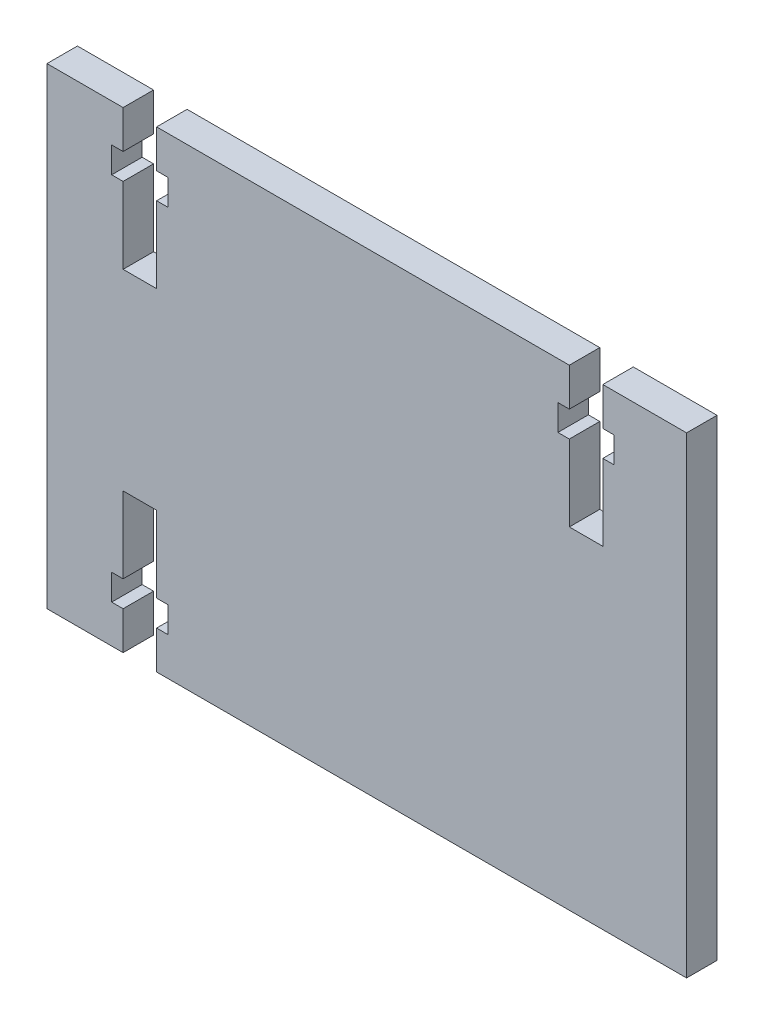
SolidWorks part; units mm, degrees
ref_plane "Front Plane" through (0, 0, 0) normal (0, 0, 1) x (1, 0, 0)
ref_plane "Top Plane" through (0, 0, 0) normal (0, 1, 0) x (1, 0, 0)
ref_plane "Right Plane" through (0, 0, 0) normal (1, 0, 0) x (0, 0, -1)
sketch "Sketch1" plane through (0, 0, 0) normal (0, 0, 1) x (1, 0, 0)
  line L1 (-41.5, 31) -> (42.5, 31)
  line L2 (-41.5, 31) -> (-41.5, -31)
  line L3 (-41.5, -31) -> (42.5, -31)
  line L4 (42.5, 31) -> (42.5, -31)
  dimension "D1" = 84
  dimension "D2" = 41.5
  dimension "D3" = 62
  dimension "D4" = 31
extrude "Boss-Extrude1" add sketch "Sketch1" along normal blind 4
sketch "Sketch2" plane through (0, 0, 4) normal (0, 0, 1) x (1, 0, 0)
  line L0 (0, 0) -> (-32.0835, 0) construction
  line L1 (42.5, -31) -> (27.5, -31)
  line L2 (42.5, -31) -> (42.5, -11)
  line L3 (42.5, -11) -> (27.5, -11)
  line L4 (27.5, -31) -> (27.5, -11)
  line L5 (0, 0) -> (0, 20.1899) construction
  dimension "D1" = 20
  dimension "D2" = 15
extrude "Cut-Extrude1" [suppressed] cut sketch "Sketch2" against normal blind 10
sketch "Sketch3" plane through (0, 0, 4) normal (0, 0, 1) x (1, 0, 0)
  line L0 (-29.3, 10.8) -> (-29.3, 25.6452) construction
  line L1 (-27.1, 22.6) -> (-27.1, 12.6)
  line L2 (-31.5, 26) -> (-31.5, 31)
  line L3 (-25.6, 26) -> (-27.1, 26)
  line L4 (-25.6, 22.6) -> (-25.6, 26)
  line L5 (-27.1, 22.6) -> (-25.6, 22.6)
  line L6 (-33, 26) -> (-31.5, 26)
  line L7 (-33, 22.6) -> (-33, 26)
  line L8 (-31.5, 22.6) -> (-33, 22.6)
  line L9 (-31.5, 12.6) -> (-27.1, 12.6)
  line L10 (-27.1, 31) -> (-27.1, 26)
  line L11 (-31.5, 31) -> (-27.1, 31)
  line L12 (-31.5, 12.6) -> (-31.5, 22.6)
  line L13 (42.5, 31) -> (-41.5, 31) construction
  line L14 (-41.5, 31) -> (-41.5, -31) construction
  line L15 (0, 0) -> (0, 26) construction
  line L16 (0, 0) -> (-34.9357, 0) construction
  line L17 (29.3, 10.8) -> (29.3, 25.6452) construction
  line L18 (31.5, 12.6) -> (31.5, 22.6)
  line L19 (31.5, 31) -> (27.1, 31)
  line L20 (27.1, 31) -> (27.1, 26)
  line L21 (31.5, 12.6) -> (27.1, 12.6)
  line L22 (31.5, 22.6) -> (33, 22.6)
  line L23 (33, 22.6) -> (33, 26)
  line L24 (33, 26) -> (31.5, 26)
  line L25 (27.1, 22.6) -> (25.6, 22.6)
  line L26 (25.6, 22.6) -> (25.6, 26)
  line L27 (25.6, 26) -> (27.1, 26)
  line L28 (31.5, 26) -> (31.5, 31)
  line L29 (27.1, 22.6) -> (27.1, 12.6)
  line L30 (-29.3, -10.8) -> (-29.3, -25.6452) construction
  line L31 (-31.5, -12.6) -> (-31.5, -22.6)
  line L32 (-31.5, -31) -> (-27.1, -31)
  line L33 (-27.1, -31) -> (-27.1, -26)
  line L34 (-31.5, -12.6) -> (-27.1, -12.6)
  line L35 (-31.5, -22.6) -> (-33, -22.6)
  line L36 (-33, -22.6) -> (-33, -26)
  line L37 (-33, -26) -> (-31.5, -26)
  line L38 (-27.1, -22.6) -> (-25.6, -22.6)
  line L39 (-25.6, -22.6) -> (-25.6, -26)
  line L40 (-25.6, -26) -> (-27.1, -26)
  line L41 (-31.5, -26) -> (-31.5, -31)
  line L42 (-27.1, -22.6) -> (-27.1, -12.6)
  dimension "D1" = 5
  dimension "D2" = 3.4
  dimension "D3" = 10
  dimension "D4" = 2.2
  dimension "D5" = 4.4
  dimension "D6" = 1.5
  dimension "D7" = 1.5
  dimension "D8" = 10
extrude "Cut-Extrude2" cut sketch "Sketch3" against normal blind 5
sketch "Sketch4" [suppressed] plane through (0, 0, 5) normal (0, 0, 1) x (1, 0, 0)
  line L1 (41.5, 31) -> (42.5, 31)
  line L2 (41.5, 31) -> (41.5, -11)
  line L3 (41.5, -11) -> (42.5, -11)
  line L4 (42.5, 31) -> (42.5, -11)
  line L5 (41.5, -11) -> (26.5, -11) construction
  dimension "D1" = 1
extrude "Boss-Extrude2" [suppressed] add sketch "Sketch4" against normal blind 5
